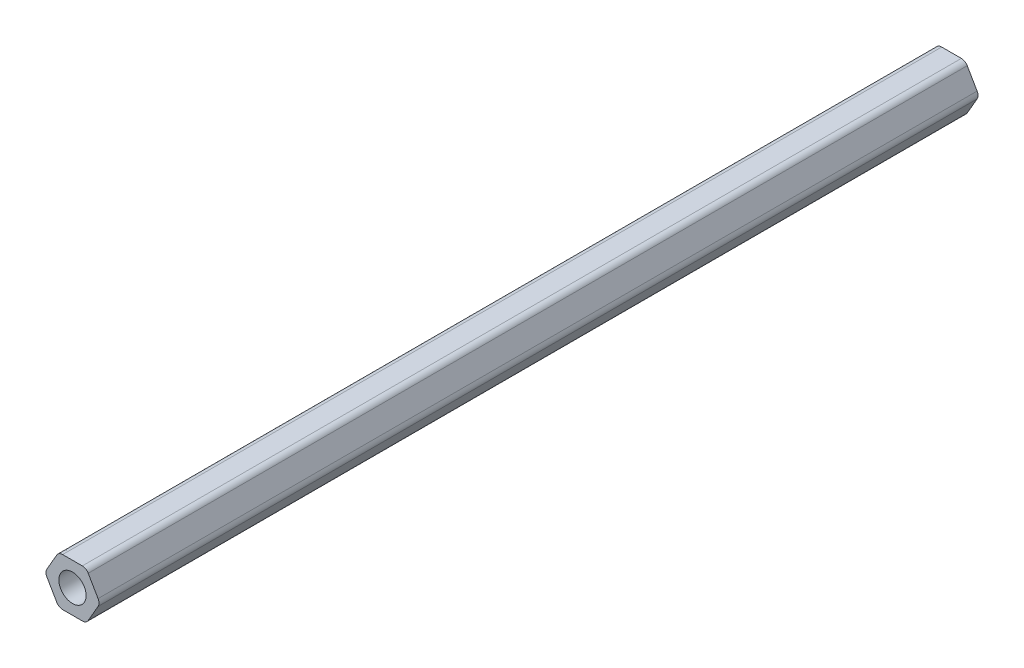
SolidWorks part; units mm, degrees
material "ABS"
ref_plane "Спереди" through (0, 0, 0) normal (0, 0, 1) x (1, 0, 0)
ref_plane "Сверху" through (0, 0, 0) normal (0, 1, 0) x (1, 0, 0)
ref_plane "Справа" through (0, 0, 0) normal (1, 0, 0) x (0, 0, -1)
sketch "Эскиз1" plane through (0, 0, 0) normal (0, 0, 1) x (1, 0, 0)
  line L1 (3.7528, 0.5) -> (2.3094, 3)
  line L2 (1.4434, 3.5) -> (-1.4434, 3.5)
  line L3 (-2.3094, 3) -> (-3.7528, 0.5)
  line L4 (-3.7528, -0.5) -> (-2.3094, -3)
  line L5 (-1.4434, -3.5) -> (1.4434, -3.5)
  line L6 (2.3094, -3) -> (3.7528, -0.5)
  circle A0 centre (0, 0) radius 3.5 construction
  circle A1 centre (0, 0) radius 2 construction
  arc A2 (-3.7528, 0.5) -> (-3.7528, -0.5) centre (-2.8868, 0) ccw
  arc A3 (-2.3094, -3) -> (-1.4434, -3.5) centre (-1.4434, -2.5) ccw
  arc A4 (1.4434, -3.5) -> (2.3094, -3) centre (1.4434, -2.5) ccw
  arc A5 (3.7528, 0.5) -> (3.7528, -0.5) centre (2.8868, 0) cw
  arc A6 (2.3094, 3) -> (1.4434, 3.5) centre (1.4434, 2.5) ccw
  arc A7 (-1.4434, 3.5) -> (-2.3094, 3) centre (-1.4434, 2.5) ccw
  dimension "D1" = 4
  dimension "D3" = 1
  dimension "D2" = 7
extrude "Бобышка-Вытянуть1" add sketch "Эскиз1" along normal blind 129
sketch "Эскиз2" plane through (0, 0, 129) normal (0, 0, 1) x (1, 0, 0)
  circle A0 centre (0, 0) radius 2
  dimension "D1" = 4
extrude "Вырез-Вытянуть1" cut sketch "Эскиз2" against normal blind 6
sketch "Эскиз3" plane through (0, 0, 0) normal (0, 0, -1) x (-1, 0, 0)
  circle A1 centre (0, 0) radius 2
  circle A2 centre (0, 0) radius 2
  dimension "D1" = 0
extrude "Вырез-Вытянуть2" cut sketch "Эскиз3" against normal blind 6
